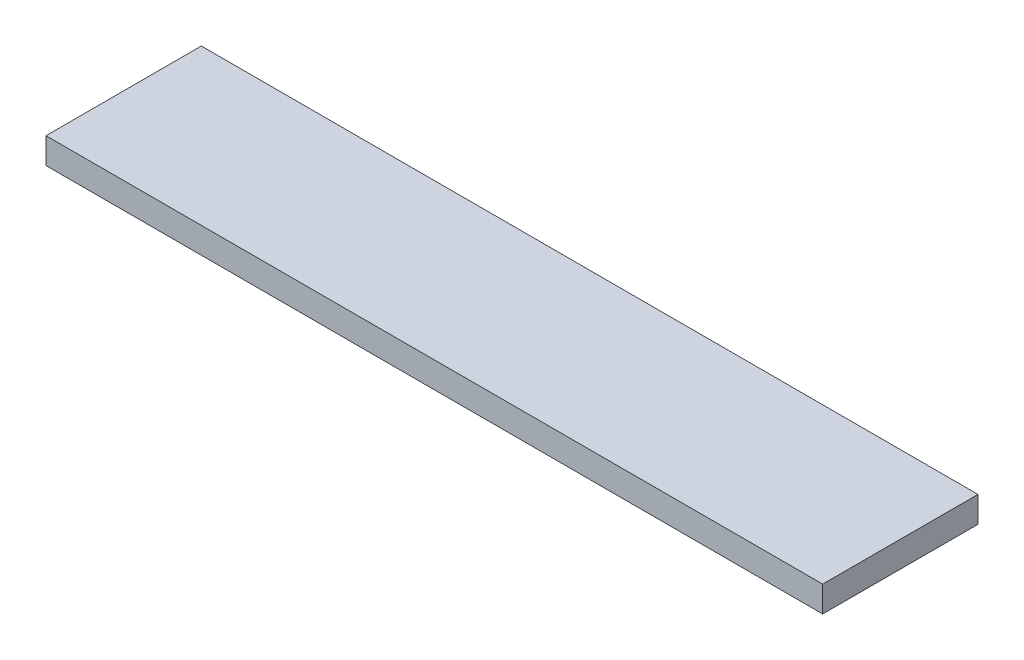
SolidWorks part; units mm, degrees
ref_plane "前基準面" through (0, 0, 0) normal (0, 0, 1) x (1, 0, 0)
ref_plane "上基準面" through (0, 0, 0) normal (0, 1, 0) x (1, 0, 0)
ref_plane "右基準面" through (0, 0, 0) normal (1, 0, 0) x (0, 0, -1)
sketch "草圖1" plane through (0, 0, 0) normal (0, 1, 0) x (1, 0, 0)
  line L1 (-150, -30) -> (150, -30)
  line L2 (-150, -30) -> (-150, 30)
  line L3 (-150, 30) -> (150, 30)
  line L4 (150, -30) -> (150, 30)
  line L5 (-150, -30) -> (150, 30) construction
  line L6 (-150, 30) -> (150, -30) construction
  point P0 (0, 0)
  dimension "D1" = 300
  dimension "D2" = 60
extrude "填料-伸長1" add sketch "草圖1" along normal blind 10
